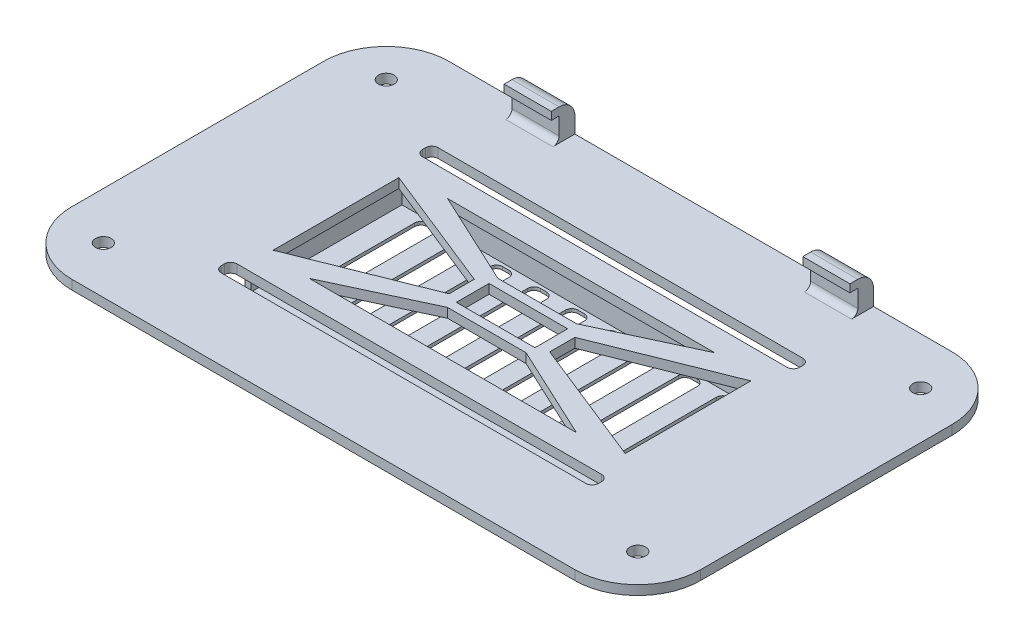
SolidWorks part; units mm, degrees
ref_plane "Front Plane" through (0, 0, 0) normal (0, 0, 1) x (1, 0, 0)
ref_plane "Top Plane" through (0, 0, 0) normal (0, 1, 0) x (1, 0, 0)
ref_plane "Right Plane" through (0, 0, 0) normal (1, 0, 0) x (0, 0, -1)
sketch "Sketch1" plane through (0, 0, 0) normal (0, 1, 0) x (1, 0, 0)
  line L1 (-100, 60) -> (100, 60)
  line L2 (-100, 60) -> (-100, -60)
  line L3 (-100, -60) -> (100, -60)
  line L4 (100, 60) -> (100, -60)
  line L5 (-100, 60) -> (100, -60) construction
  line L6 (-100, -60) -> (100, 60) construction
  point P0 (0, 0)
  dimension "D1" = 120
  dimension "D2" = 200
extrude "Boss-Extrude1" add sketch "Sketch1" along normal blind 3
sketch "Sketch2" plane through (0, 0, 0) normal (0, -1, 0) x (1, 0, 0)
  line L1 (-60, 25) -> (60, 25)
  line L2 (-60, 25) -> (-60, -25)
  line L3 (-60, -25) -> (60, -25)
  line L4 (60, 25) -> (60, -25)
  line L5 (-60, 25) -> (60, -25) construction
  line L6 (-60, -25) -> (60, 25) construction
  point P0 (0, 0)
  dimension "D1" = 50
  dimension "D2" = 120
extrude "Boss-Extrude2" add sketch "Sketch2" along normal blind 8
sketch "Sketch3" plane through (0, 0, 25) normal (0, 0, 1) x (1, 0, 0)
  line L0 (-60, -8) -> (60, 0) construction
  line L2 (-58, -1) -> (58, -1)
  line L3 (-58, -1) -> (-58, -7)
  line L4 (-58, -7) -> (58, -7)
  line L5 (58, -1) -> (58, -7)
  line L6 (-58, -1) -> (58, -7) construction
  line L7 (-58, -7) -> (58, -1) construction
  line L9 (-58, -1) -> (-58, 0)
  line L10 (60, 0) -> (-60, 0) construction
  line L11 (-58, 0) -> (58, 0)
  line L12 (58, 0) -> (58, -1)
  point P4 (0, -4)
  line M6 (60, 0) -> (-60, 0)
  dimension "D1" = 116
  dimension "D2" = 6
extrude "Cut-Extrude2" cut sketch "Sketch3" against normal blind 48 contours L12 L9 L2 M6 | L5 L2 L3 L4
sketch "Sketch4" plane through (0, 3, 0) normal (0, 1, 0) x (1, 0, 0)
  line L0 (0, 0) -> (0, -8) construction
  line L1 (-60, 25) -> (60, 25)
  line L2 (-60, 25) -> (-60, -25)
  line L3 (-60, -25) -> (60, -25)
  line L4 (60, 25) -> (60, -25)
  line L5 (-60, 25) -> (60, -25) construction
  line L6 (-60, -25) -> (60, 25) construction
  line L7 (-12.5, 5.2083) -> (12.5, 5.2083)
  line L8 (-12.5, 5.2083) -> (-12.5, -5.2083)
  line L9 (-12.5, -5.2083) -> (12.5, -5.2083)
  line L10 (12.5, 5.2083) -> (12.5, -5.2083)
  line L11 (-12.5, 5.2083) -> (12.5, -5.2083) construction
  line L12 (-12.5, -5.2083) -> (12.5, 5.2083) construction
  line L13 (-12.5, -8) -> (12.5, -8)
  line L14 (0, -8) -> (0, -22) construction
  line L15 (-42.5, -22) -> (42.5, -22)
  line L16 (-12.5, -8) -> (-42.5, -22)
  line L17 (12.5, -8) -> (42.5, -22)
  line L18 (0, 0) -> (60, 0) construction
  line L19 (-12.5, 8) -> (12.5, 8)
  line L20 (-12.5, 8) -> (-42.5, 22)
  line L21 (-42.5, 22) -> (42.5, 22)
  line L22 (12.5, 8) -> (42.5, 22)
  line L23 (0, 0) -> (-16, 0) construction
  line L24 (-16, 4) -> (-16, -4)
  line L25 (-16, 0) -> (-56, 0)
  line L26 (-56, 20) -> (-56, -20)
  line L27 (-56, -20) -> (-16, -4)
  line L28 (-56, 20) -> (-16, 4)
  line L29 (56, 20) -> (56, -20)
  line L30 (56, -20) -> (16, -4)
  line L31 (16, 4) -> (16, -4)
  line L32 (56, 20) -> (16, 4)
  point P0 (0, 0)
  point P6 (0, 0)
  point P15 (0, -8)
  point P16 (0, -8)
  point P20 (0, -22)
  point P30 (-16, 0)
  point P34 (-56, 0)
  dimension "D1" = 120
  dimension "D2" = 50
  dimension "D3" = 14
  dimension "D4" = 22
extrude "Cut-Extrude3" cut sketch "Sketch4" against normal blind 4 contours L17 L13 L16 L15 | L29 L32 L31 L30 | L19 L22 L21 L20 | L10 L7 L8 L9 | L26 L27 L24 L25 | L28 L26 L25 L24
sketch "Sketch5" plane through (0, -8, 0) normal (0, -1, 0) x (1, 0, 0)
  line L0 (9, 20) -> (9, -20)
  line L1 (-1, 22) -> (1, 22)
  line L2 (-3, 20) -> (-3, -20)
  line L3 (-1, -22) -> (1, -22)
  line L4 (3, 20) -> (3, -20)
  line L5 (-3, 22) -> (3, -22) construction
  line L6 (-3, -22) -> (3, 22) construction
  line L7 (11, 22) -> (13, 22)
  line L8 (15, 20) -> (15, -20)
  line L9 (11, -22) -> (13, -22)
  line L10 (21, 20) -> (21, -20)
  line L11 (23, 22) -> (25, 22)
  line L12 (27, 20) -> (27, -20)
  line L13 (23, -22) -> (25, -22)
  line L14 (33, 20) -> (33, -20)
  line L15 (35, 22) -> (37, 22)
  line L16 (39, 20) -> (39, -20)
  line L17 (35, -22) -> (37, -22)
  line L18 (45, 20) -> (45, -20)
  line L19 (47, 22) -> (49, 22)
  line L20 (51, 20) -> (51, -20)
  line L21 (47, -22) -> (49, -22)
  line L22 (-15, 20) -> (-15, -20)
  line L23 (-13, 22) -> (-11, 22)
  line L24 (-9, 20) -> (-9, -20)
  line L25 (-13, -22) -> (-11, -22)
  line L26 (-27, 20) -> (-27, -20)
  line L27 (-25, 22) -> (-23, 22)
  line L28 (-21, 20) -> (-21, -20)
  line L29 (-25, -22) -> (-23, -22)
  line L30 (-39, 20) -> (-39, -20)
  line L31 (-37, 22) -> (-35, 22)
  line L32 (-33, 20) -> (-33, -20)
  line L33 (-37, -22) -> (-35, -22)
  line L34 (-51, 20) -> (-51, -20)
  line L35 (-49, 22) -> (-47, 22)
  line L36 (-45, 20) -> (-45, -20)
  line L37 (-49, -22) -> (-47, -22)
  arc A0 (1, -22) -> (3, -20) centre (1, -20) ccw
  arc A1 (-1, -22) -> (-3, -20) centre (-1, -20) cw
  arc A2 (1, 22) -> (3, 20) centre (1, 20) cw
  arc A3 (-3, 20) -> (-1, 22) centre (-1, 20) cw
  arc A4 (9, 20) -> (11, 22) centre (11, 20) cw
  arc A5 (11, -22) -> (9, -20) centre (11, -20) cw
  arc A6 (13, 22) -> (15, 20) centre (13, 20) cw
  arc A7 (13, -22) -> (15, -20) centre (13, -20) ccw
  arc A8 (21, 20) -> (23, 22) centre (23, 20) cw
  arc A9 (23, -22) -> (21, -20) centre (23, -20) cw
  arc A10 (25, 22) -> (27, 20) centre (25, 20) cw
  arc A11 (25, -22) -> (27, -20) centre (25, -20) ccw
  arc A12 (33, 20) -> (35, 22) centre (35, 20) cw
  arc A13 (35, -22) -> (33, -20) centre (35, -20) cw
  arc A14 (37, 22) -> (39, 20) centre (37, 20) cw
  arc A15 (37, -22) -> (39, -20) centre (37, -20) ccw
  arc A16 (45, 20) -> (47, 22) centre (47, 20) cw
  arc A17 (47, -22) -> (45, -20) centre (47, -20) cw
  arc A18 (49, 22) -> (51, 20) centre (49, 20) cw
  arc A19 (49, -22) -> (51, -20) centre (49, -20) ccw
  arc A20 (-15, 20) -> (-13, 22) centre (-13, 20) cw
  arc A21 (-13, -22) -> (-15, -20) centre (-13, -20) cw
  arc A22 (-11, 22) -> (-9, 20) centre (-11, 20) cw
  arc A23 (-11, -22) -> (-9, -20) centre (-11, -20) ccw
  arc A24 (-27, 20) -> (-25, 22) centre (-25, 20) cw
  arc A25 (-25, -22) -> (-27, -20) centre (-25, -20) cw
  arc A26 (-23, 22) -> (-21, 20) centre (-23, 20) cw
  arc A27 (-23, -22) -> (-21, -20) centre (-23, -20) ccw
  arc A28 (-39, 20) -> (-37, 22) centre (-37, 20) cw
  arc A29 (-37, -22) -> (-39, -20) centre (-37, -20) cw
  arc A30 (-35, 22) -> (-33, 20) centre (-35, 20) cw
  arc A31 (-35, -22) -> (-33, -20) centre (-35, -20) ccw
  arc A32 (-51, 20) -> (-49, 22) centre (-49, 20) cw
  arc A33 (-49, -22) -> (-51, -20) centre (-49, -20) cw
  arc A34 (-47, 22) -> (-45, 20) centre (-47, 20) cw
  arc A35 (-47, -22) -> (-45, -20) centre (-47, -20) ccw
  point P0 (0, 0)
  dimension "D3" = 2
  dimension "D1" = 6
  dimension "D2" = 44
  dimension "D4" = 5
  dimension "D5" = 5
extrude "Cut-Extrude4" cut sketch "Sketch5" against normal blind 4
fillet "Fillet1" radius 20 4 edges at (100, 1.5, 60) (-100, 1.5, 60) (-100, 1.5, -60) (100, 1.5, -60)
sketch "Sketch6" plane through (0, 3, 0) normal (0, 1, 0) x (1, 0, 0)
  line L0 (0, 0) -> (0, 60)
  line L1 (80, 60) -> (-80, 60) construction
  line L2 (0, 60) -> (-55, 60)
  line L4 (-55, 60) -> (-40, 60)
  line L5 (-55, 60) -> (-55, 52.5)
  line L6 (-55, 52.5) -> (-40, 52.5)
  line L7 (-40, 60) -> (-40, 52.5)
  dimension "D1" = 7.5
  dimension "D2" = 15
extrude "Boss-Extrude3" add sketch "Sketch6" along normal blind 10 contours L5 L4 L7 L6
sketch "Sketch7" plane through (-55, 0, 0) normal (-1, 0, 0) x (0, 0, 1)
  line L0 (-52.5, 13) -> (-52.5, 10.5)
  line L1 (-52.5, 13) -> (-52.5, 3) construction
  line L2 (-52.5, 10.5) -> (-55, 10.5)
  line L3 (-55, 10.5) -> (-55, 3)
  line L4 (-40, 3) -> (-60, 3) construction
  line L5 (-55, 3) -> (-60, 3)
  line L6 (-60, 3) -> (-52.5, 3) construction
  line L7 (-60, 3) -> (-60, 13)
  line L8 (-60, 13) -> (-52.5, 13)
  line M7 (-60, 3) -> (-52.5, 3)
  line M8 (-52.5, 3) -> (-52.5, 13)
  dimension "D1" = 2.5
  dimension "D2" = 5
extrude "Cut-Extrude5" cut sketch "Sketch7" against normal blind 17 contours L2 L3 M7 M8
fillet "Fillet4" radius 2 1 edges at (-47.5, 3, -55)
fillet "Fillet5" radius 5 1 edges at (-47.5, 13, -60)
sketch "Sketch8" plane through (0, 3, 0) normal (0, 1, 0) x (1, 0, 0)
  line L0 (0, 0) -> (0, 32)
  line L1 (0, 0) -> (56, 0)
  line L2 (-58, 34.5) -> (58, 34.5)
  line L3 (-60, 32.5) -> (-60, 31.5)
  line L4 (-58, 29.5) -> (58, 29.5)
  line L5 (60, 32.5) -> (60, 31.5)
  line L6 (-60, 34.5) -> (60, 29.5) construction
  line L7 (-60, 29.5) -> (60, 34.5) construction
  line L8 (56, 20) -> (56, -20) construction
  line L9 (-60, -29.5) -> (60, -29.5)
  line L10 (60, -34.5) -> (60, -29.5)
  line L11 (-60, -34.5) -> (60, -34.5)
  line L12 (-60, -34.5) -> (-60, -29.5)
  arc A0 (60, 32.5) -> (58, 34.5) centre (58, 32.5) ccw
  arc A1 (58, 29.5) -> (60, 31.5) centre (58, 31.5) ccw
  arc A2 (-60, 31.5) -> (-58, 29.5) centre (-58, 31.5) ccw
  arc A3 (-58, 34.5) -> (-60, 32.5) centre (-58, 32.5) ccw
  dimension "D4" = 2
  dimension "D1" = 32
  dimension "D2" = 5
  dimension "D3" = 120
extrude "Cut-Extrude6" cut sketch "Sketch8" against normal blind 10
mirror "Mirror1" about plane through (0, 0, 0) normal (0, 0, 1) of "Cut-Extrude6"
mirror "Mirror3" about plane through (0, 0, 0) normal (1, 0, 0) of "Fillet4", "Cut-Extrude5", "Boss-Extrude3", "Fillet5"
sketch "Sketch10" plane through (0, 3, 0) normal (0, 1, 0) x (1, 0, 0)
  line L0 (0, 0) -> (85, 0) construction
  line L1 (85, 0) -> (85, -45) construction
  circle A0 centre (85, -45) radius 2.5
  dimension "D3" = 5
  dimension "D1" = 85
  dimension "D2" = 45
extrude "Cut-Extrude7" cut sketch "Sketch10" against normal blind 15
mirror "Mirror4" about plane through (0, 0, 0) normal (1, 0, 0) of "Cut-Extrude7"
mirror "Mirror5" about plane through (0, 0, 0) normal (0, 0, 1) of "Mirror4", "Cut-Extrude7"
